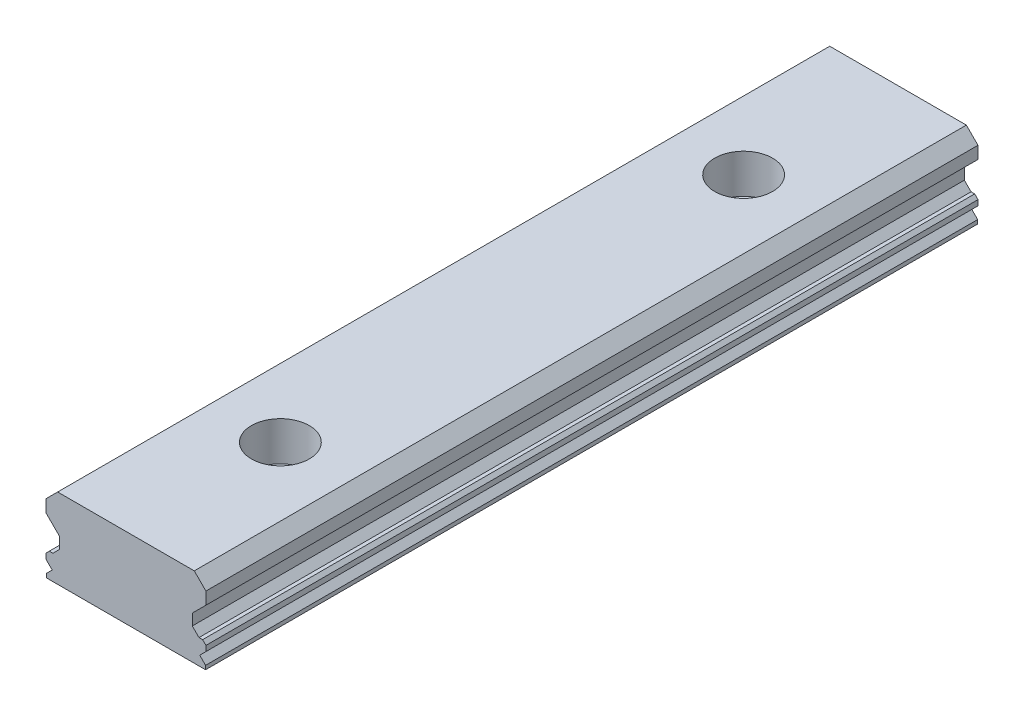
SolidWorks part; units mm, degrees
ref_plane "前视基准面" through (0, 0, 0) normal (0, 0, 1) x (1, 0, 0)
ref_plane "上视基准面" through (0, 0, 0) normal (0, 1, 0) x (1, 0, 0)
ref_plane "右视基准面" through (0, 0, 0) normal (1, 0, 0) x (0, 0, -1)
sketch "Sketch4" plane through (0, 0, 0) normal (0, 0, 1) x (1, 0, 0)
  line L24 (-9.0549, 5.7851) -> (9.0549, 5.7851)
  line L35 (-10.8561, -3.2254) -> (-10.2614, -3.8202)
  line L36 (-10.8561, -2.1135) -> (-10.8561, -3.2254)
  line L37 (-10.1346, -1.392) -> (-10.8561, -2.1135)
  line L38 (-9.6666, -1.392) -> (-10.1346, -1.392)
  line L39 (-9.0919, -0.8173) -> (-9.6666, -1.392)
  line L40 (-9.0919, 0.2129) -> (-9.0919, -0.8173)
  line L41 (-10.8561, 1.9772) -> (-9.0919, 0.2129)
  line L42 (-10.8561, 3.9838) -> (-10.8561, 1.9772)
  line L43 (-9.0549, 5.7851) -> (-10.8561, 3.9838)
  line L46 (14.3201, 10.9812) -> (-14.3201, 10.9812)
  line L47 (-14.3201, 10.9812) -> (-17, 8.3013)
  line L48 (-17, 8.3013) -> (-17, -2.9179)
  line L49 (-17, -2.9179) -> (-15.6924, -4.2255)
  line L55 (-10.2614, -3.8202) -> (-10.6667, -4.2255)
  line L56 (-10.6667, -4.2255) -> (-15.6924, -4.2255)
  line L59 (0, 5.7851) -> (0, 10.9812) construction
  line L60 (10.6667, -4.2255) -> (15.6924, -4.2255)
  line L61 (10.2614, -3.8202) -> (10.6667, -4.2255)
  line L62 (17, -2.9179) -> (15.6924, -4.2255)
  line L63 (17, 8.3013) -> (17, -2.9179)
  line L64 (14.3201, 10.9812) -> (17, 8.3013)
  line L65 (9.0549, 5.7851) -> (10.8561, 3.9838)
  line L66 (10.8561, 3.9838) -> (10.8561, 1.9772)
  line L67 (10.8561, 1.9772) -> (9.0919, 0.2129)
  line L68 (9.0919, 0.2129) -> (9.0919, -0.8173)
  line L69 (9.0919, -0.8173) -> (9.6666, -1.392)
  line L70 (9.6666, -1.392) -> (10.1346, -1.392)
  line L71 (10.1346, -1.392) -> (10.8561, -2.1135)
  line L72 (10.8561, -2.1135) -> (10.8561, -3.2254)
  line L73 (10.8561, -3.2254) -> (10.2614, -3.8202)
sketch "Sketch1" plane through (0, 0, 0) normal (0, 0, 1) x (1, 0, 0)
  line L296 (-10.3132, -4.5791) -> (-10.3132, -5.0791)
  line L297 (-10.3132, -5.0791) -> (10.3132, -5.0791)
  line L298 (10.3132, -5.0791) -> (10.3132, -4.5791)
  line L317 (10.3132, -4.5791) -> (9.5543, -3.8202)
  line L318 (9.5543, -3.8202) -> (10.3561, -3.0183)
  line L319 (10.3561, -3.0183) -> (10.3561, -2.3206)
  line L320 (10.3561, -2.3206) -> (9.9275, -1.892)
  line L321 (9.9275, -1.892) -> (9.4595, -1.892)
  line L322 (9.4595, -1.892) -> (8.5919, -1.0244)
  line L323 (8.5919, -1.0244) -> (8.5919, 0.42)
  line L324 (8.5919, 0.42) -> (10.3561, 2.1843)
  line L325 (10.3561, 2.1843) -> (10.3561, 3.7767)
  line L326 (10.3561, 3.7767) -> (8.8478, 5.2851)
  line L327 (8.8478, 5.2851) -> (-8.8478, 5.2851)
  line L328 (-8.8478, 5.2851) -> (-10.3561, 3.7767)
  line L329 (-10.3561, 3.7767) -> (-10.3561, 2.1843)
  line L330 (-10.3561, 2.1843) -> (-8.5919, 0.42)
  line L331 (-8.5919, 0.42) -> (-8.5919, -1.0244)
  line L332 (-8.5919, -1.0244) -> (-9.4595, -1.892)
  line L333 (-9.4595, -1.892) -> (-9.9275, -1.892)
  line L334 (-9.9275, -1.892) -> (-10.3561, -2.3206)
  line L335 (-10.3561, -2.3206) -> (-10.3561, -3.0183)
  line L336 (-10.3561, -3.0183) -> (-9.5543, -3.8202)
  line L337 (-9.5543, -3.8202) -> (-10.3132, -4.5791)
  line L338 (10.3132, -4.5791) -> (9.5543, -3.8202)
  line L339 (9.5543, -3.8202) -> (10.3561, -3.0183)
  line L340 (10.3561, -3.0183) -> (10.3561, -2.3206)
  line L341 (10.3561, -2.3206) -> (9.9275, -1.892)
  line L342 (9.9275, -1.892) -> (9.4595, -1.892)
  line L343 (9.4595, -1.892) -> (8.5919, -1.0244)
  line L344 (8.5919, -1.0244) -> (8.5919, 0.42)
  line L345 (8.5919, 0.42) -> (10.3561, 2.1843)
  line L346 (10.3561, 2.1843) -> (10.3561, 3.7767)
  line L347 (10.3561, 3.7767) -> (8.8478, 5.2851)
  line L348 (8.8478, 5.2851) -> (-8.8478, 5.2851)
  line L349 (-8.8478, 5.2851) -> (-10.3561, 3.7767)
  line L350 (-10.3561, 3.7767) -> (-10.3561, 2.1843)
  line L351 (-10.3561, 2.1843) -> (-8.5919, 0.42)
  line L352 (-8.5919, 0.42) -> (-8.5919, -1.0244)
  line L353 (-8.5919, -1.0244) -> (-9.4595, -1.892)
  line L354 (-9.4595, -1.892) -> (-9.9275, -1.892)
  line L355 (-9.9275, -1.892) -> (-10.3561, -2.3206)
  line L356 (-10.3561, -2.3206) -> (-10.3561, -3.0183)
  line L357 (-10.3561, -3.0183) -> (-9.5543, -3.8202)
  line L358 (-9.5543, -3.8202) -> (-10.3132, -4.5791)
  dimension "D1" = 0.5
extrude "Boss-Extrude1" add sketch "Sketch1" along normal blind 100
sketch "Sketch2" plane through (0, 5.2851, 0) normal (0, 1, 0) x (1, 0, 0)
  line L1 (-9.0549, 0) -> (9.0549, 0) construction
  circle A0 centre (0, -20) radius 3.75
  circle A6 centre (0, -80) radius 3.75
  dimension "D1" = 7.5
  dimension "D2" = 20
  dimension "D3" = 2
extrude "Cut-Extrude1" cut sketch "Sketch2" against normal offset from surface (5.0641 mm away) 5.3 up to face at (0, -5.0791, 50)
sketch "Sketch3" plane through (0, 0.2209, 0) normal (0, 1, 0) x (1, 0, 0)
  circle A0 centre (0, -20) radius 2.25
  circle A6 centre (0, -80) radius 2.25
  dimension "D1" = 4.5
  dimension "D2" = 4.5
extrude "Cut-Extrude2" cut sketch "Sketch3" against normal through all
